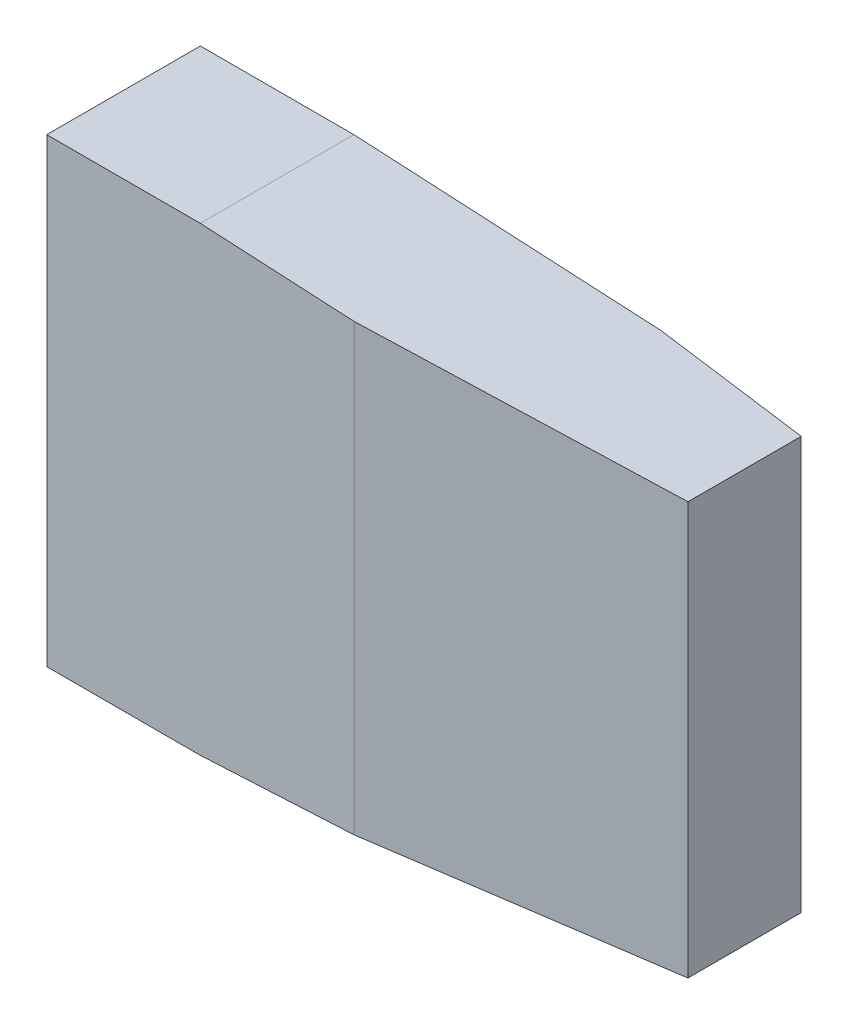
SolidWorks part; units mm, degrees
ref_plane "前视基准面" through (0, 0, 0) normal (0, 0, 1) x (1, 0, 0)
ref_plane "上视基准面" through (0, 0, 0) normal (0, 1, 0) x (1, 0, 0)
ref_plane "右视基准面" through (0, 0, 0) normal (1, 0, 0) x (0, 0, -1)
other "Configuration Table"
sketch "草图1" plane through (0, 0, 0) normal (0, 1, 0) x (1, 0, 0)
  line L1 (-100, -25) -> (100, -25)
  line L2 (-100, -25) -> (-100, 25)
  line L3 (-100, 25) -> (100, 25)
  line L4 (100, -25) -> (100, 25)
  line L5 (-100, -25) -> (100, 25) construction
  line L6 (-100, 25) -> (100, -25) construction
  point P0 (0, 0)
  dimension "D1" = 200
  dimension "D2" = 50
extrude "凸台-拉伸1" add sketch "草图1" along normal mid plane 150
chamfer "倒角1" distance 100 angle 5 1 edges at (100, 0, 25)
chamfer "倒角2" distance 50 angle 5 1 edges at (100, 0, -25)
chamfer "倒角3" distance 150 angle 3 1 edges at (100, -75, -2.1872)
chamfer "倒角4" distance 150 angle 3 1 edges at (100, 75, -2.1872)
sketch "草图2" plane through (0, 0, -25) normal (0, 0, -1) x (-1, 0, 0)
  line L0 (100, 75) -> (100, -75) construction
  line L1 (50, 75) -> (100, 75) construction
  circle A0 centre (12, 0) radius 8
  dimension "D3" = 16
  dimension "D1" = 88
  dimension "D2" = 75
extrude "切除-拉伸1" cut sketch "草图2" against normal blind 5
